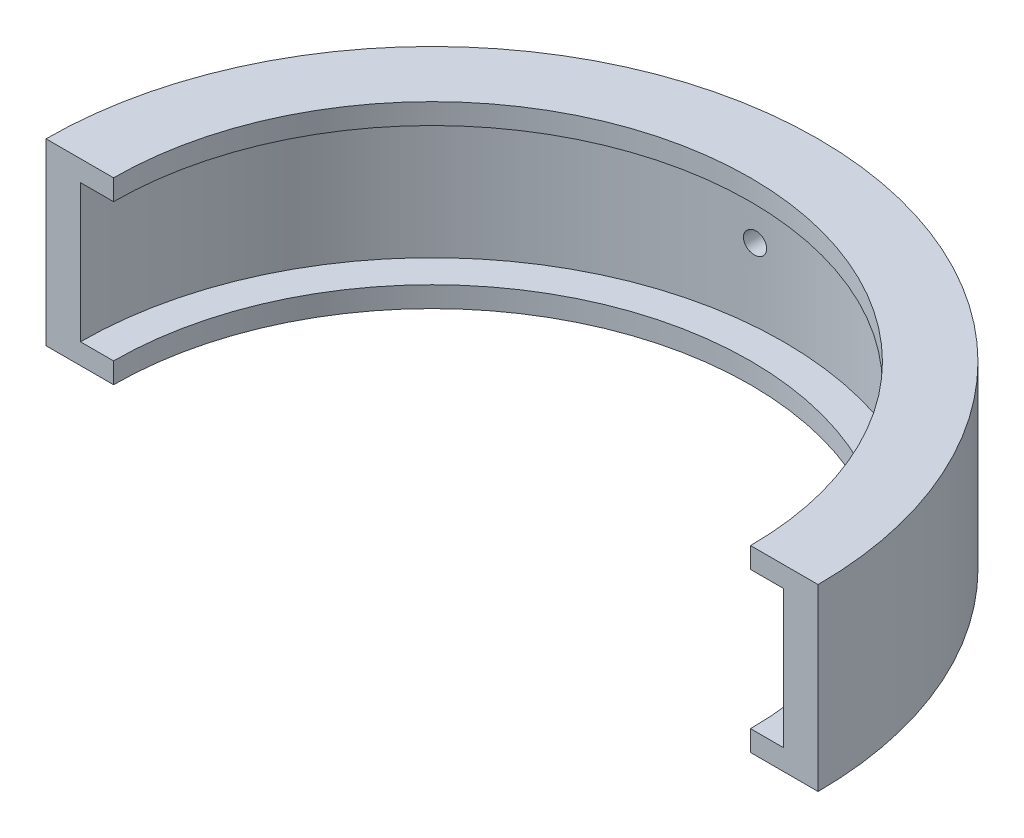
SolidWorks part; units mm, degrees
ref_plane "Front Plane" through (0, 0, 0) normal (0, 0, 1) x (1, 0, 0)
ref_plane "Top Plane" through (0, 0, 0) normal (0, 1, 0) x (1, 0, 0)
ref_plane "Right Plane" through (0, 0, 0) normal (1, 0, 0) x (0, 0, -1)
sketch "Sketch1" plane through (0, 0, 0) normal (0, 0, 1) x (1, 0, 0)
  line L0 (-4.9719, -11.985) -> (4.4455, -11.985)
  line L1 (4.4455, -11.985) -> (4.4455, -9.1021)
  line L2 (4.4455, -9.1021) -> (-0.1671, -9.1021)
  line L3 (-0.1671, -9.1021) -> (-0.1671, 10.1171)
  line L4 (-0.1671, 10.1171) -> (4.4455, 10.1171)
  line L5 (4.4455, 10.1171) -> (4.4455, 13)
  line L6 (4.4455, 13) -> (-4.9719, 13)
  line L7 (-4.9719, 13) -> (-4.9719, -11.985)
  line L8 (48.842, -11.985) -> (48.842, 13) construction
revolve "Revolve1" add sketch "Sketch1" angle 180 about L8
ref_plane "Plane1" through (0, 0, -54) normal (0, 0, 1) x (1, 0, 0)
sketch "Sketch2" plane through (0, 0, -54) normal (0, 0, 1) x (1, 0, 0)
  line L0 (93.2385, 13) -> (4.4455, 13) construction
  line L1 (-4.9719, 13) -> (-4.9719, -11.985) construction
  circle A0 centre (45.0281, 1) radius 1.5
  dimension "D1" = 12
  dimension "D2" = 50
extrude "Cut-Extrude1" cut sketch "Sketch2" along normal blind 21
